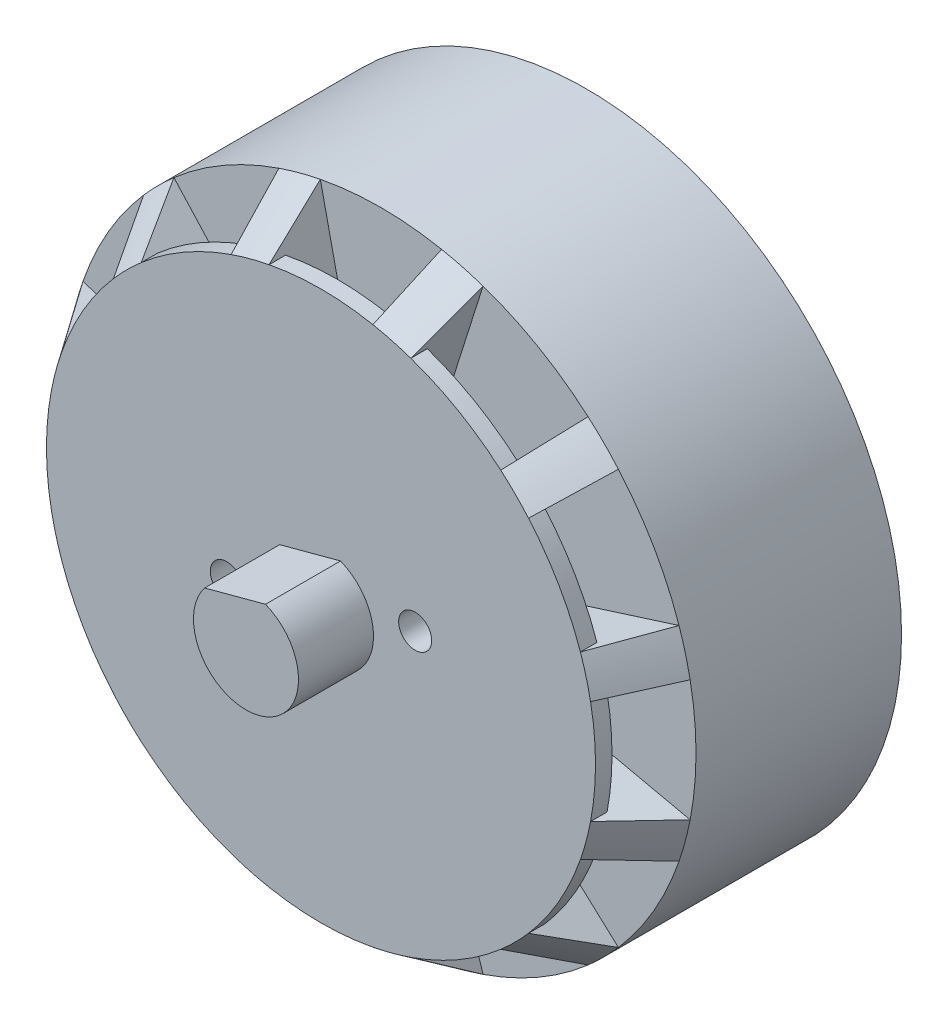
SolidWorks part; units mm, degrees
ref_plane "前视基准面" through (0, 0, 0) normal (0, 0, 1) x (1, 0, 0)
ref_plane "上视基准面" through (0, 0, 0) normal (0, 1, 0) x (1, 0, 0)
ref_plane "右视基准面" through (0, 0, 0) normal (1, 0, 0) x (0, 0, -1)
sketch "草图1" plane through (0, 0, 0) normal (0, 0, 1) x (1, 0, 0)
  circle A0 centre (0, 0) radius 21
  dimension "D1" = 42
extrude "凸台-拉伸1" add sketch "草图1" along normal blind 13.7
ref_plane "基准面1" through (0, 0, 17.7) normal (0, 0, 1) x (1, 0, 0)
sketch "草图2" plane through (0, 0, 17.7) normal (0, 0, 1) x (1, 0, 0)
  circle A0 centre (0, 0) radius 18.3
  dimension "D1" = 36.6
sketch "草图3" plane through (0, 0, 13.7) normal (0, 0, 1) x (1, 0, 0)
  circle A0 centre (0, 0) radius 21
  dimension "D1" = 42
loft "放样1" add profiles "草图3", "草图2"
sketch "草图4" plane through (0, 0, 17.7) normal (0, 0, 1) x (1, 0, 0)
  line L0 (0, 0) -> (21, 0) construction
  line L1 (0, 0) -> (20.2844, 5.4352)
  line L2 (0, 0) -> (20.2844, -5.4352)
  line L3 (20.6075, 4.0413) -> (6.9242, 1.0271)
  line L4 (20.6075, -4.0413) -> (6.9242, -1.0271)
  circle A0 centre (0, 0) radius 21 construction
  circle A1 centre (0, 0) radius 7
  circle A2 centre (0, 0) radius 21
  dimension "D2" = 14
  dimension "D1" = 15
  dimension "D3" = 1.4308
  dimension "D4" = 0.8
extrude "切除-拉伸1" cut sketch "草图4" against normal blind 4
pattern_circular "阵列(圆周)1" count 12 over 360 about axis through (0, 0, 0) along (0, 0, 1) of "切除-拉伸1"
sketch "草图5" plane through (0, 0, 17.7) normal (0, 0, 1) x (1, 0, 0)
  circle A0 centre (0, 0) radius 18.3
  dimension "D1" = 36.6
extrude "凸台-拉伸2" add sketch "草图5" against normal blind 1.1
sketch "草图6" plane through (0, 0, 17.7) normal (0, 0, 1) x (1, 0, 0)
  line L0 (-2.7531, 2.1611) -> (1.3038, 3.2481)
  line L1 (20.2844, 5.4352) -> (-20.2844, -5.4352) construction
  arc A0 (-2.7531, 2.1611) -> (1.3038, 3.2481) centre (0, 0) ccw
  arc A1 (20.6075, 4.0413) -> (19.8672, 6.8039) centre (0, 0) ccw construction
  arc A2 (-20.6075, -4.0413) -> (-19.8672, -6.8039) centre (0, 0) ccw construction
  dimension "D1" = 7
  dimension "D2" = 2.8
extrude "凸台-拉伸3" add sketch "草图6" along normal blind 5
sketch "草图8" plane through (0, 0, 17.7) normal (0, 0, 1) x (1, 0, 0)
  line L0 (20.2844, 5.4352) -> (-20.2844, -5.4352) construction
  line L1 (-5.4352, 20.2844) -> (0, 0) construction
  arc A0 (20.6075, 4.0413) -> (19.8672, 6.8039) centre (0, 0) ccw construction
  arc A1 (-20.6075, -4.0413) -> (-19.8672, -6.8039) centre (0, 0) ccw construction
  arc A2 (-4.0413, 20.6075) -> (-6.8039, 19.8672) centre (0, 0) ccw construction
  circle A3 centre (6.2785, 1.6823) radius 3
  circle A4 centre (-6.2785, -1.6823) radius 3
  dimension "D1" = 6
  dimension "D2" = 13
extrude "凸台-拉伸4" add sketch "草图8" against normal blind 4
sketch "草图9" plane through (0, 0, 17.7) normal (0, 0, 1) x (1, 0, 0)
  circle A0 centre (6.2785, 1.6823) radius 1.1
  circle A1 centre (-6.2785, -1.6823) radius 1.1
  dimension "D1" = 2.2
  dimension "D2" = 2.2
extrude "切除-拉伸3" cut sketch "草图9" against normal blind 4
cosmetic thread "装饰螺纹线1" parameters "D2"=3
cosmetic thread "装饰螺纹线2" parameters "D2"=3
